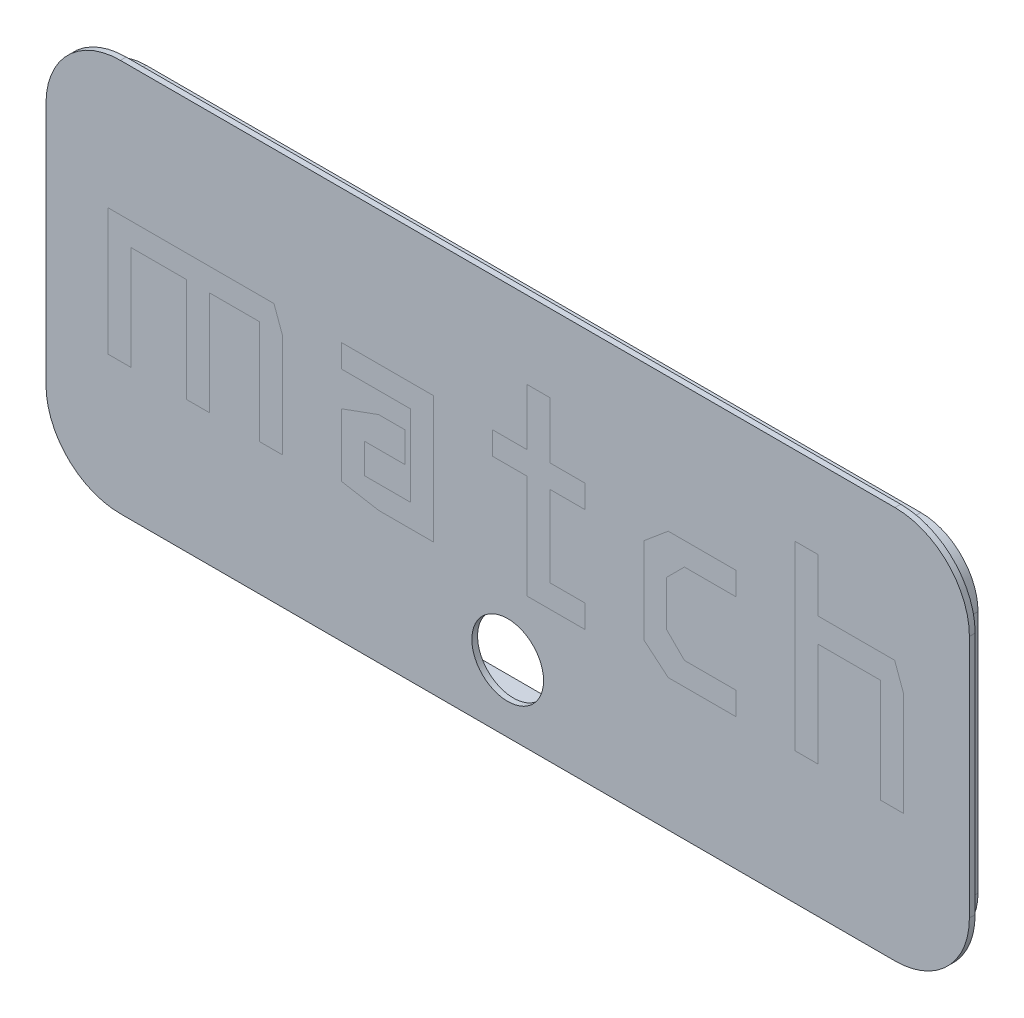
SolidWorks part; units mm, degrees
ref_plane "Ebene vorne" through (0, 0, 0) normal (0, 0, 1) x (1, 0, 0)
ref_plane "Ebene oben" through (0, 0, 0) normal (0, 1, 0) x (1, 0, 0)
ref_plane "Ebene rechts" through (0, 0, 0) normal (1, 0, 0) x (0, 0, -1)
sketch "Skizze1" plane through (0, 0, 1.6001) normal (0, 0, 1) x (1, 0, 0)
  line L0 (-27.8511, -4.4825) -> (-26.2511, -4.4825)
  line L1 (-26.2511, -4.4825) -> (-26.2511, 2.7565)
  line L2 (-26.2511, 2.7565) -> (-22.39, 2.7565)
  line L3 (-22.39, 2.7565) -> (-22.39, -4.4825)
  line L4 (-22.39, -4.4825) -> (-20.79, -4.4825)
  line L5 (-20.79, -4.4825) -> (-20.79, 2.7565)
  line L6 (-20.79, 2.7565) -> (-17.31, 2.7565)
  line L7 (-17.31, 2.7565) -> (-17.31, -4.4825)
  line L8 (-17.31, -4.4825) -> (-15.71, -4.4825)
  line L10 (-16.2924, 4.3565) -> (-27.8511, 4.3565)
  line L11 (-27.8511, 4.3565) -> (-27.8511, -4.4825)
  line L24 (-11.595, 4.3565) -> (-5.169, 4.3565)
  line L25 (-5.169, 4.3565) -> (-5.169, -4.4825)
  line L26 (-5.169, -4.4825) -> (-8.995, -4.4825)
  line L27 (-8.995, -4.4825) -> (-11.595, -4.0241)
  line L28 (-11.595, -4.0241) -> (-11.595, 0.3551)
  line L29 (-11.595, 0.3551) -> (-8.995, 1.3014)
  line L31 (-7.1585, -0.7995) -> (-9.995, -0.7995)
  line L32 (-9.995, -0.7995) -> (-9.995, -2.8825)
  line L33 (-9.995, -2.8825) -> (-6.769, -2.8825)
  line L34 (-6.769, -2.8825) -> (-6.769, 2.7565)
  line L35 (-6.769, 2.7565) -> (-11.595, 2.7565)
  line L36 (-11.595, 2.7565) -> (-11.595, 4.3565)
  line L50 (1.359, 8.2935) -> (1.359, 4.3565)
  line L51 (1.359, 4.3565) -> (-1.054, 4.3565)
  line L52 (-1.054, 4.3565) -> (-1.054, 2.7565)
  line L53 (-1.054, 2.7565) -> (1.359, 2.7565)
  line L54 (1.359, 2.7565) -> (1.359, -4.4825)
  line L55 (1.359, -4.4825) -> (5.372, -4.4825)
  line L56 (5.372, -4.4825) -> (5.372, -2.8825)
  line L57 (5.372, -2.8825) -> (2.959, -2.8825)
  line L58 (2.959, -2.8825) -> (2.959, 2.7565)
  line L59 (2.959, 2.7565) -> (5.372, 2.7565)
  line L60 (5.372, 2.7565) -> (5.372, 4.3565)
  line L61 (5.372, 4.3565) -> (2.959, 4.3565)
  line L62 (2.959, 4.3565) -> (2.959, 8.2935)
  line L63 (2.959, 8.2935) -> (1.359, 8.2935)
  line L64 (-16.01, 0.6435) -> (-16.01, 1.6435) construction
  line L65 (-27.5511, 4.0565) -> (-27.5511, 3.0565) construction
  line L66 (-26.5511, -1.7695) -> (-26.5511, -0.7695) construction
  line L67 (-22.09, 1.6435) -> (-22.09, 0.6435) construction
  line L68 (-21.09, 0.6435) -> (-21.09, 1.6435) construction
  line L69 (-20.312, 3.0565) -> (-19.312, 3.0565) construction
  line L70 (-15.71, 2.7565) -> (-16.2924, 4.3565)
  line L71 (-24.138, 4.0565) -> (-25.138, 4.0565) construction
  line L72 (-27.5511, -4.1825) -> (-26.5511, -4.1825) construction
  line L73 (-17.01, 1.6435) -> (-17.01, 0.6435) construction
  line L74 (20.028, 8.1665) -> (20.028, -4.4825)
  line L75 (20.028, -4.4825) -> (21.628, -4.4825)
  line L76 (21.628, -4.4825) -> (21.628, 2.7565)
  line L77 (21.628, 2.7565) -> (25.9971, 2.7565)
  line L78 (25.9971, 2.7565) -> (25.9971, -4.4825)
  line L79 (25.9971, -4.4825) -> (27.5971, -4.4825)
  line L80 (27.5971, -4.4825) -> (27.5971, 2.7565)
  line L83 (26.9783, 4.4565) -> (21.628, 4.4565)
  line L84 (21.628, 4.4565) -> (21.628, 8.1665)
  line L85 (21.628, 8.1665) -> (20.028, 8.1665)
  line L86 (15.913, 2.7565) -> (12.3216, 2.7565)
  line L87 (12.3216, 2.7565) -> (11.087, 1.5219)
  line L88 (11.087, 1.5219) -> (11.087, -1.6479)
  line L89 (11.087, -1.6479) -> (12.3216, -2.8825)
  line L90 (12.3216, -2.8825) -> (15.913, -2.8825)
  line L91 (15.913, -2.8825) -> (15.913, -4.4825)
  line L92 (15.913, -4.4825) -> (11.1914, -4.4825)
  line L93 (11.1914, -4.4825) -> (9.487, -3.0524)
  line L94 (9.487, -3.0524) -> (9.487, 2.9264)
  line L95 (9.487, 2.9264) -> (11.1914, 4.3565)
  line L96 (11.1914, 4.3565) -> (15.913, 4.3565)
  line L97 (15.913, 4.3565) -> (15.913, 2.7565)
  line L98 (-0.754, 4.0565) -> (-0.754, 3.0565) construction
  line L99 (0.246, 4.0565) -> (-0.754, 4.0565) construction
  line L100 (1.659, 5.1995) -> (1.659, 4.1995) construction
  line L101 (2.659, 7.9935) -> (1.659, 7.9935) construction
  line L102 (2.659, 6.9935) -> (2.659, 7.9935) construction
  line L103 (5.072, 3.0565) -> (5.072, 4.0565) construction
  line L104 (4.072, 3.0565) -> (5.072, 3.0565) construction
  line L105 (2.659, 1.4055) -> (2.659, 2.4055) construction
  line L106 (5.072, -4.1825) -> (5.072, -3.1825) construction
  line L107 (5.072, -3.1825) -> (4.072, -3.1825) construction
  line L108 (1.659, -4.1825) -> (2.659, -4.1825) construction
  line L109 (9.787, 0.3735) -> (9.787, -0.6265) construction
  line L110 (10.787, -0.6265) -> (10.787, 0.3735) construction
  line L111 (-11.295, 4.0565) -> (-11.295, 3.0565) construction
  line L112 (-10.295, 4.0565) -> (-11.295, 4.0565) construction
  line L113 (14.613, 3.0565) -> (15.613, 3.0565) construction
  line L114 (15.613, 3.0565) -> (15.613, 4.0565) construction
  line L115 (13.2, 4.0565) -> (12.2, 4.0565) construction
  line L116 (12.2, -4.1825) -> (13.2, -4.1825) construction
  line L117 (20.328, -0.2615) -> (20.328, -1.2615) construction
  line L118 (21.328, -1.2615) -> (21.328, -0.2615) construction
  line L119 (22.741, 3.0565) -> (23.741, 3.0565) construction
  line L120 (26.2971, 1.7705) -> (26.2971, 0.7705) construction
  line L121 (27.2971, 0.7705) -> (27.2971, 1.7705) construction
  line L122 (23.741, 4.0565) -> (22.741, 4.0565) construction
  line L123 (21.328, 7.8665) -> (20.328, 7.8665) construction
  line L124 (21.328, 6.8665) -> (21.328, 7.8665) construction
  line L125 (27.5971, 2.7565) -> (26.9783, 4.4565)
  line L126 (20.328, -4.1825) -> (21.328, -4.1825) construction
  line L127 (-15.71, -4.4825) -> (-15.71, 2.7565)
  line L129 (-11.295, 3.0565) -> (-10.295, 3.0565) construction
  line L130 (-11.295, -0.1345) -> (-11.295, -1.1345) construction
  line L131 (-8.882, -4.1825) -> (-7.882, -4.1825) construction
  line L132 (-5.469, 3.0565) -> (-5.469, 4.0565) construction
  line L134 (-6.469, 1.6435) -> (-6.469, 0.6435) construction
  line L135 (-7.882, -3.1825) -> (-8.882, -3.1825) construction
  line L136 (-10.295, -1.1345) -> (-10.295, -0.1345) construction
  line L137 (-8.995, 1.3014) -> (-7.1585, 1.3014)
  line L138 (-7.1585, 1.3014) -> (-7.1585, -0.7995)
  line L140 (-7.755, 0.5005) -> (-8.755, 0.5005) construction
  line L141 (-4.569, 4.7565) -> (-11.995, 4.7565)
  line L142 (-4.569, 4.7565) -> (-4.569, -5.0825)
  line L143 (-4.569, -5.0825) -> (-11.995, -5.0825)
  line L144 (-11.995, 4.7565) -> (-11.995, -5.0825)
  line L145 (-7.755, -0.4995) -> (-7.755, 0.5005) construction
  line L146 (-8.755, -0.4995) -> (-7.755, -0.4995) construction
  line L147 (-15.9423, 4.8565) -> (-28.3511, 4.8565)
  line L148 (-28.3511, 4.8565) -> (-28.3511, -4.9825)
  line L149 (-28.3511, -4.9825) -> (-25.7511, -4.9825)
  line L150 (-25.7511, -4.9825) -> (-25.7511, 2.2565)
  line L151 (-25.7511, 2.2565) -> (-22.89, 2.2565)
  line L152 (-22.89, 2.2565) -> (-22.89, -4.9825)
  line L153 (-22.89, -4.9825) -> (-20.29, -4.9825)
  line L154 (-20.29, -4.9825) -> (-20.29, 2.2565)
  line L155 (-20.29, 2.2565) -> (-17.81, 2.2565)
  line L156 (-17.81, 2.2565) -> (-17.81, -4.9825)
  line L157 (-17.81, -4.9825) -> (-15.21, -4.9825)
  line L158 (-15.21, -4.9825) -> (-15.21, 2.8447)
  line L159 (-15.21, 2.8447) -> (-15.9423, 4.8565)
  line L160 (5.872, 4.8565) -> (3.459, 4.8565)
  line L161 (3.459, 4.8565) -> (3.459, 8.7935)
  line L162 (3.459, 8.7935) -> (0.859, 8.7935)
  line L163 (0.859, 8.7935) -> (0.859, 4.8565)
  line L164 (0.859, 4.8565) -> (-1.554, 4.8565)
  line L165 (-1.554, 4.8565) -> (-1.554, 2.2565)
  line L166 (-1.554, 2.2565) -> (0.859, 2.2565)
  line L167 (0.859, 2.2565) -> (0.859, -4.9825)
  line L168 (0.859, -4.9825) -> (5.872, -4.9825)
  line L169 (5.872, -4.9825) -> (5.872, -2.3825)
  line L170 (5.872, -2.3825) -> (3.459, -2.3825)
  line L171 (3.459, -2.3825) -> (3.459, 2.2565)
  line L172 (3.459, 2.2565) -> (5.872, 2.2565)
  line L173 (5.872, 2.2565) -> (5.872, 4.8565)
  line L174 (11.0094, 4.8565) -> (16.413, 4.8565)
  line L175 (16.413, 4.8565) -> (16.413, 2.2565)
  line L176 (16.413, 2.2565) -> (12.5287, 2.2565)
  line L177 (12.5287, 2.2565) -> (11.587, 1.3148)
  line L178 (11.587, 1.3148) -> (11.587, -1.4408)
  line L179 (11.587, -1.4408) -> (12.5287, -2.3825)
  line L180 (12.5287, -2.3825) -> (16.413, -2.3825)
  line L181 (16.413, -2.3825) -> (16.413, -4.9825)
  line L182 (16.413, -4.9825) -> (11.0094, -4.9825)
  line L183 (11.0094, -4.9825) -> (8.987, -3.2856)
  line L184 (8.987, -3.2856) -> (8.987, 3.1596)
  line L185 (8.987, 3.1596) -> (11.0094, 4.8565)
  line L186 (27.2584, 4.8565) -> (22.028, 4.8565)
  line L187 (22.028, 4.8565) -> (22.028, 8.5665)
  line L188 (22.028, 8.5665) -> (19.628, 8.5665)
  line L189 (19.628, 8.5665) -> (19.628, -4.8825)
  line L190 (19.628, -4.8825) -> (22.028, -4.8825)
  line L191 (22.028, -4.8825) -> (22.028, 2.3565)
  line L192 (22.028, 2.3565) -> (25.5971, 2.3565)
  line L193 (25.5971, 2.3565) -> (25.5971, -4.8825)
  line L194 (25.5971, -4.8825) -> (27.9971, -4.8825)
  line L195 (27.9971, -4.8825) -> (27.9971, 2.827)
  line L196 (27.9971, 2.827) -> (27.2584, 4.8565)
  dimension "D1" = 0.3
  dimension "D2" = 0.3
  dimension "D3" = 0.3
  dimension "D4" = 0.3
  dimension "D5" = 0.3
  dimension "D7" = 0.3
  dimension "D8" = 0.3
  dimension "D9" = 0.3
  dimension "D10" = 0.3
  dimension "D11" = 0.3
  dimension "D12" = 0.3
  dimension "D13" = 0.3
  dimension "D14" = 0.3
  dimension "D15" = 0.3
  dimension "D16" = 0.3
  dimension "D17" = 0.3
  dimension "D18" = 0.3
  dimension "D19" = 0.3
  dimension "D20" = 0.3
  dimension "D21" = 0.3
  dimension "D22" = 0.3
  dimension "D23" = 0.3
  dimension "D24" = 0.3
  dimension "D25" = 0.3
  dimension "D26" = 0.3
  dimension "D27" = 130
  dimension "D28" = 135
  dimension "D29" = 0.4
  dimension "D30" = 0.3
  dimension "D31" = 0.3
  dimension "D32" = 0.3
  dimension "D33" = 0.3
  dimension "D34" = 0.3
  dimension "D35" = 0.3
  dimension "D36" = 0.4
  dimension "D37" = 0.3
  dimension "D38" = 0.3
  dimension "D39" = 20
  dimension "D40" = 0.3
  dimension "D6" = 0.3
  dimension "D41" = 200
  dimension "D42" = 0.3
  dimension "D43" = 0.3
  dimension "D44" = 0.3
  dimension "D45" = 0.3
  dimension "D46" = 0.3
  dimension "D47" = 0.3
  dimension "D48" = 0.3
  dimension "D49" = 0.3
  dimension "D50" = 0.3
  dimension "D51" = 110
  dimension "D52" = 0.8009
  dimension "D53" = 0.5965
  dimension "D54" = 0.3
  dimension "D55" = 2.6
  dimension "D56" = 0.4
  dimension "D58" = 0.6
  dimension "D59" = 0.4
  dimension "D57" = 10
  dimension "D64" = 2.6
  dimension "D65" = 0.6
  dimension "D60" = 0.5
  dimension "D61" = 0.5
  dimension "D62" = 0.5
  dimension "D63" = 0.4
extrude "Aufsatz-Linear austragen1" add sketch "Skizze1" along normal blind 1.4
sketch "Skizze2" plane through (0, 0, 3.0001) normal (0, 0, 1) x (1, 0, 0)
  line L0 (30.9874, 8.5) -> (30.9874, -8.5) construction
  line L1 (27.0001, -12.4873) -> (-27.0001, -12.4873) construction
  line L2 (-30.9874, -8.5) -> (-30.9874, 8.5) construction
  line L3 (-27.0001, 12.4873) -> (27.0001, 12.4873) construction
  line L4 (30.9874, 8.5) -> (30.9874, -8.5) construction
  line L5 (27.0001, -12.4873) -> (-27.0001, -12.4873) construction
  line L6 (-30.9874, -8.5) -> (-30.9874, 8.5) construction
  line L7 (-27.0001, 12.4873) -> (27.0001, 12.4873) construction
  line L8 (-27.0001, 13.6873) -> (27.0001, 13.6873)
  line L9 (32.1874, 8.5) -> (32.1874, -8.5)
  line L10 (27.0001, -13.6873) -> (-27.0001, -13.6873)
  line L11 (-32.1874, -8.5) -> (-32.1874, 8.5)
  arc A0 (30.9874, 8.5) -> (27.0001, 12.4873) centre (27.0001, 8.5) ccw construction
  arc A1 (27.0001, -12.4873) -> (30.9874, -8.5) centre (27.0001, -8.5) ccw construction
  arc A2 (-30.9874, -8.5) -> (-27.0001, -12.4873) centre (-27.0001, -8.5) ccw construction
  arc A3 (-27.0001, 12.4873) -> (-30.9874, 8.5) centre (-27.0001, 8.5) ccw construction
  arc A4 (30.9874, 8.5) -> (27.0001, 12.4873) centre (27.0001, 8.5) ccw construction
  arc A5 (27.0001, -12.4873) -> (30.9874, -8.5) centre (27.0001, -8.5) ccw construction
  arc A6 (-30.9874, -8.5) -> (-27.0001, -12.4873) centre (-27.0001, -8.5) ccw construction
  arc A7 (-27.0001, 12.4873) -> (-30.9874, 8.5) centre (-27.0001, 8.5) ccw construction
  circle A8 centre (0, -9.017) radius 2.5
  arc A9 (0.7218, -9.017) -> (-0.7218, -9.017) centre (0, -9.017) ccw construction
  arc A10 (0.7218, -9.017) -> (-0.7218, -9.017) centre (0, -9.017) ccw construction
  arc A11 (32.1874, 8.5) -> (27.0001, 13.6873) centre (27.0001, 8.5) ccw
  arc A12 (27.0001, -13.6873) -> (32.1874, -8.5) centre (27.0001, -8.5) ccw
  arc A13 (-32.1874, -8.5) -> (-27.0001, -13.6873) centre (-27.0001, -8.5) ccw
  arc A14 (-27.0001, 13.6873) -> (-32.1874, 8.5) centre (-27.0001, 8.5) ccw
  dimension "D1" = 5
  dimension "D2" = 1.2
extrude "Aufsatz-Linear austragen2" add sketch "Skizze2" along normal blind 0.4
sketch "Skizze3" plane through (0, 0, 3.0001) normal (0, 0, -1) x (-1, 0, 0)
  line L0 (-30.9874, 8.5) -> (-30.9874, -8.5) construction
  line L1 (-27.0001, -12.4873) -> (27.0001, -12.4873) construction
  line L2 (30.9874, -8.5) -> (30.9874, 8.5) construction
  line L3 (27.0001, 12.4873) -> (-27.0001, 12.4873) construction
  line L4 (-30.9874, 8.5) -> (-30.9874, -8.5)
  line L5 (-27.0001, -12.4873) -> (27.0001, -12.4873)
  line L6 (30.9874, -8.5) -> (30.9874, 8.5)
  line L7 (27.0001, 12.4873) -> (-27.0001, 12.4873)
  line L8 (27.0001, 11.6873) -> (-27.0001, 11.6873)
  line L9 (-30.1874, 8.5) -> (-30.1874, -8.5)
  line L10 (-27.0001, -11.6873) -> (27.0001, -11.6873)
  line L11 (30.1874, -8.5) -> (30.1874, 8.5)
  arc A0 (-27.0001, 12.4873) -> (-30.9874, 8.5) centre (-27.0001, 8.5) ccw construction
  arc A1 (-30.9874, -8.5) -> (-27.0001, -12.4873) centre (-27.0001, -8.5) ccw construction
  arc A2 (27.0001, -12.4873) -> (30.9874, -8.5) centre (27.0001, -8.5) ccw construction
  arc A3 (30.9874, 8.5) -> (27.0001, 12.4873) centre (27.0001, 8.5) ccw construction
  arc A4 (-27.0001, 12.4873) -> (-30.9874, 8.5) centre (-27.0001, 8.5) ccw
  arc A5 (-30.9874, -8.5) -> (-27.0001, -12.4873) centre (-27.0001, -8.5) ccw
  arc A6 (27.0001, -12.4873) -> (30.9874, -8.5) centre (27.0001, -8.5) ccw
  arc A7 (30.9874, 8.5) -> (27.0001, 12.4873) centre (27.0001, 8.5) ccw
  arc A8 (-27.0001, 11.6873) -> (-30.1874, 8.5) centre (-27.0001, 8.5) ccw
  arc A9 (-30.1874, -8.5) -> (-27.0001, -11.6873) centre (-27.0001, -8.5) ccw
  arc A10 (27.0001, -11.6873) -> (30.1874, -8.5) centre (27.0001, -8.5) ccw
  arc A11 (30.1874, 8.5) -> (27.0001, 11.6873) centre (27.0001, 8.5) ccw
  dimension "D1" = 0.8
extrude "Aufsatz-Linear austragen3" add sketch "Skizze3" along normal up to surface (1.4 mm away)
sketch "Skizze6" plane through (0, 0, 3.4001) normal (0, 0, 1) x (1, 0, 0)
  line L0 (-26.2511, -4.4825) -> (-27.8511, -4.4825) construction
  line L1 (-27.8511, -4.4825) -> (-27.8511, 4.3565) construction
  line L2 (-27.8511, 4.3565) -> (-16.2924, 4.3565) construction
  line L3 (-16.2924, 4.3565) -> (-15.71, 2.7565) construction
  line L4 (-15.71, 2.7565) -> (-15.71, -4.4825) construction
  line L5 (-15.71, -4.4825) -> (-17.31, -4.4825) construction
  line L6 (-17.31, -4.4825) -> (-17.31, 2.7565) construction
  line L7 (-17.31, 2.7565) -> (-20.79, 2.7565) construction
  line L8 (-20.79, 2.7565) -> (-20.79, -4.4825) construction
  line L9 (-20.79, -4.4825) -> (-22.39, -4.4825) construction
  line L10 (-22.39, -4.4825) -> (-22.39, 2.7565) construction
  line L11 (-22.39, 2.7565) -> (-26.2511, 2.7565) construction
  line L12 (-26.2511, 2.7565) -> (-26.2511, -4.4825) construction
  line L13 (-7.1585, 1.3014) -> (-7.1585, -0.7995) construction
  line L14 (-7.1585, -0.7995) -> (-9.995, -0.7995) construction
  line L15 (-9.995, -0.7995) -> (-9.995, -2.8825) construction
  line L16 (-9.995, -2.8825) -> (-6.769, -2.8825) construction
  line L17 (-6.769, -2.8825) -> (-6.769, 2.7565) construction
  line L18 (-6.769, 2.7565) -> (-11.595, 2.7565) construction
  line L19 (-11.595, 2.7565) -> (-11.595, 4.3565) construction
  line L20 (-11.595, 4.3565) -> (-5.169, 4.3565) construction
  line L21 (-5.169, 4.3565) -> (-5.169, -4.4825) construction
  line L22 (-5.169, -4.4825) -> (-8.995, -4.4825) construction
  line L23 (-8.995, -4.4825) -> (-11.595, -4.0241) construction
  line L24 (-11.595, -4.0241) -> (-11.595, 0.3551) construction
  line L25 (-11.595, 0.3551) -> (-8.995, 1.3014) construction
  line L26 (-8.995, 1.3014) -> (-7.1585, 1.3014) construction
  line L27 (1.359, 4.3565) -> (1.359, 8.2935) construction
  line L28 (1.359, 8.2935) -> (2.959, 8.2935) construction
  line L29 (2.959, 8.2935) -> (2.959, 4.3565) construction
  line L30 (2.959, 4.3565) -> (5.372, 4.3565) construction
  line L31 (5.372, 4.3565) -> (5.372, 2.7565) construction
  line L32 (5.372, 2.7565) -> (2.959, 2.7565) construction
  line L33 (2.959, 2.7565) -> (2.959, -2.8825) construction
  line L34 (2.959, -2.8825) -> (5.372, -2.8825) construction
  line L35 (5.372, -2.8825) -> (5.372, -4.4825) construction
  line L36 (5.372, -4.4825) -> (1.359, -4.4825) construction
  line L37 (1.359, -4.4825) -> (1.359, 2.7565) construction
  line L38 (1.359, 2.7565) -> (-1.054, 2.7565) construction
  line L39 (-1.054, 2.7565) -> (-1.054, 4.3565) construction
  line L40 (-1.054, 4.3565) -> (1.359, 4.3565) construction
  line L41 (11.1914, 4.3565) -> (15.913, 4.3565) construction
  line L42 (15.913, 4.3565) -> (15.913, 2.7565) construction
  line L43 (15.913, 2.7565) -> (12.3216, 2.7565) construction
  line L44 (12.3216, 2.7565) -> (11.087, 1.5219) construction
  line L45 (11.087, 1.5219) -> (11.087, -1.6479) construction
  line L46 (11.087, -1.6479) -> (12.3216, -2.8825) construction
  line L47 (12.3216, -2.8825) -> (15.913, -2.8825) construction
  line L48 (15.913, -2.8825) -> (15.913, -4.4825) construction
  line L49 (15.913, -4.4825) -> (11.1914, -4.4825) construction
  line L50 (11.1914, -4.4825) -> (9.487, -3.0524) construction
  line L51 (9.487, -3.0524) -> (9.487, 2.9264) construction
  line L52 (9.487, 2.9264) -> (11.1914, 4.3565) construction
  line L53 (20.028, -4.4825) -> (20.028, 8.1665) construction
  line L54 (20.028, 8.1665) -> (21.628, 8.1665) construction
  line L55 (21.628, 8.1665) -> (21.628, 4.4565) construction
  line L56 (21.628, 4.4565) -> (26.9783, 4.4565) construction
  line L57 (26.9783, 4.4565) -> (27.5971, 2.7565) construction
  line L58 (27.5971, 2.7565) -> (27.5971, -4.4825) construction
  line L59 (27.5971, -4.4825) -> (25.9971, -4.4825) construction
  line L60 (25.9971, -4.4825) -> (25.9971, 2.7565) construction
  line L61 (25.9971, 2.7565) -> (21.628, 2.7565) construction
  line L62 (21.628, 2.7565) -> (21.628, -4.4825) construction
  line L63 (21.628, -4.4825) -> (20.028, -4.4825) construction
  line L64 (-26.2511, -4.4825) -> (-27.8511, -4.4825)
  line L65 (-27.8511, -4.4825) -> (-27.8511, 4.3565)
  line L66 (-27.8511, 4.3565) -> (-16.2924, 4.3565)
  line L67 (-16.2924, 4.3565) -> (-15.71, 2.7565)
  line L68 (-15.71, 2.7565) -> (-15.71, -4.4825)
  line L69 (-15.71, -4.4825) -> (-17.31, -4.4825)
  line L70 (-17.31, -4.4825) -> (-17.31, 2.7565)
  line L71 (-17.31, 2.7565) -> (-20.79, 2.7565)
  line L72 (-20.79, 2.7565) -> (-20.79, -4.4825)
  line L73 (-20.79, -4.4825) -> (-22.39, -4.4825)
  line L74 (-22.39, -4.4825) -> (-22.39, 2.7565)
  line L75 (-22.39, 2.7565) -> (-26.2511, 2.7565)
  line L76 (-26.2511, 2.7565) -> (-26.2511, -4.4825)
  line L77 (-7.1585, 1.3014) -> (-7.1585, -0.7995)
  line L78 (-7.1585, -0.7995) -> (-9.995, -0.7995)
  line L79 (-9.995, -0.7995) -> (-9.995, -2.8825)
  line L80 (-9.995, -2.8825) -> (-6.769, -2.8825)
  line L81 (-6.769, -2.8825) -> (-6.769, 2.7565)
  line L82 (-6.769, 2.7565) -> (-11.595, 2.7565)
  line L83 (-11.595, 2.7565) -> (-11.595, 4.3565)
  line L84 (-11.595, 4.3565) -> (-5.169, 4.3565)
  line L85 (-5.169, 4.3565) -> (-5.169, -4.4825)
  line L86 (-5.169, -4.4825) -> (-8.995, -4.4825)
  line L87 (-8.995, -4.4825) -> (-11.595, -4.0241)
  line L88 (-11.595, -4.0241) -> (-11.595, 0.3551)
  line L89 (-11.595, 0.3551) -> (-8.995, 1.3014)
  line L90 (-8.995, 1.3014) -> (-7.1585, 1.3014)
  line L91 (1.359, 4.3565) -> (1.359, 8.2935)
  line L92 (1.359, 8.2935) -> (2.959, 8.2935)
  line L93 (2.959, 8.2935) -> (2.959, 4.3565)
  line L94 (2.959, 4.3565) -> (5.372, 4.3565)
  line L95 (5.372, 4.3565) -> (5.372, 2.7565)
  line L96 (5.372, 2.7565) -> (2.959, 2.7565)
  line L97 (2.959, 2.7565) -> (2.959, -2.8825)
  line L98 (2.959, -2.8825) -> (5.372, -2.8825)
  line L99 (5.372, -2.8825) -> (5.372, -4.4825)
  line L100 (5.372, -4.4825) -> (1.359, -4.4825)
  line L101 (1.359, -4.4825) -> (1.359, 2.7565)
  line L102 (1.359, 2.7565) -> (-1.054, 2.7565)
  line L103 (-1.054, 2.7565) -> (-1.054, 4.3565)
  line L104 (-1.054, 4.3565) -> (1.359, 4.3565)
  line L105 (11.1914, 4.3565) -> (15.913, 4.3565)
  line L106 (15.913, 4.3565) -> (15.913, 2.7565)
  line L107 (15.913, 2.7565) -> (12.3216, 2.7565)
  line L108 (12.3216, 2.7565) -> (11.087, 1.5219)
  line L109 (11.087, 1.5219) -> (11.087, -1.6479)
  line L110 (11.087, -1.6479) -> (12.3216, -2.8825)
  line L111 (12.3216, -2.8825) -> (15.913, -2.8825)
  line L112 (15.913, -2.8825) -> (15.913, -4.4825)
  line L113 (15.913, -4.4825) -> (11.1914, -4.4825)
  line L114 (11.1914, -4.4825) -> (9.487, -3.0524)
  line L115 (9.487, -3.0524) -> (9.487, 2.9264)
  line L116 (9.487, 2.9264) -> (11.1914, 4.3565)
  line L117 (20.028, -4.4825) -> (20.028, 8.1665)
  line L118 (20.028, 8.1665) -> (21.628, 8.1665)
  line L119 (21.628, 8.1665) -> (21.628, 4.4565)
  line L120 (21.628, 4.4565) -> (26.9783, 4.4565)
  line L121 (26.9783, 4.4565) -> (27.5971, 2.7565)
  line L122 (27.5971, 2.7565) -> (27.5971, -4.4825)
  line L123 (27.5971, -4.4825) -> (25.9971, -4.4825)
  line L124 (25.9971, -4.4825) -> (25.9971, 2.7565)
  line L125 (25.9971, 2.7565) -> (21.628, 2.7565)
  line L126 (21.628, 2.7565) -> (21.628, -4.4825)
  line L127 (21.628, -4.4825) -> (20.028, -4.4825)
sketch "Skizze4" plane through (0, 0, 3.0001) normal (0, 0, -1) x (-1, 0, 0)
  line L0 (26.2511, -4.4825) -> (27.8511, -4.4825) construction
  line L1 (27.8511, -4.4825) -> (27.8511, 4.3565) construction
  line L2 (27.8511, 4.3565) -> (16.2924, 4.3565) construction
  line L3 (16.2924, 4.3565) -> (15.71, 2.7565) construction
  line L4 (15.71, 2.7565) -> (15.71, -4.4825) construction
  line L5 (15.71, -4.4825) -> (17.31, -4.4825) construction
  line L6 (17.31, -4.4825) -> (17.31, 2.7565) construction
  line L7 (17.31, 2.7565) -> (20.79, 2.7565) construction
  line L8 (20.79, 2.7565) -> (20.79, -4.4825) construction
  line L9 (20.79, -4.4825) -> (22.39, -4.4825) construction
  line L10 (22.39, -4.4825) -> (22.39, 2.7565) construction
  line L11 (22.39, 2.7565) -> (26.2511, 2.7565) construction
  line L12 (26.2511, 2.7565) -> (26.2511, -4.4825) construction
  line L13 (7.1585, 1.3014) -> (7.1585, -0.7995) construction
  line L14 (7.1585, -0.7995) -> (9.995, -0.7995) construction
  line L15 (9.995, -0.7995) -> (9.995, -2.8825) construction
  line L16 (9.995, -2.8825) -> (6.769, -2.8825) construction
  line L17 (6.769, -2.8825) -> (6.769, 2.7565) construction
  line L18 (6.769, 2.7565) -> (11.595, 2.7565) construction
  line L19 (11.595, 2.7565) -> (11.595, 4.3565) construction
  line L20 (11.595, 4.3565) -> (5.169, 4.3565) construction
  line L21 (5.169, 4.3565) -> (5.169, -4.4825) construction
  line L22 (5.169, -4.4825) -> (8.995, -4.4825) construction
  line L23 (8.995, -4.4825) -> (11.595, -4.0241) construction
  line L24 (11.595, -4.0241) -> (11.595, 0.3551) construction
  line L25 (11.595, 0.3551) -> (8.995, 1.3014) construction
  line L26 (8.995, 1.3014) -> (7.1585, 1.3014) construction
  line L27 (-1.359, 4.3565) -> (-1.359, 8.2935) construction
  line L28 (-1.359, 8.2935) -> (-2.959, 8.2935) construction
  line L29 (-2.959, 8.2935) -> (-2.959, 4.3565) construction
  line L30 (-2.959, 4.3565) -> (-5.372, 4.3565) construction
  line L31 (-5.372, 4.3565) -> (-5.372, 2.7565) construction
  line L32 (-5.372, 2.7565) -> (-2.959, 2.7565) construction
  line L33 (-2.959, 2.7565) -> (-2.959, -2.8825) construction
  line L34 (-2.959, -2.8825) -> (-5.372, -2.8825) construction
  line L35 (-5.372, -2.8825) -> (-5.372, -4.4825) construction
  line L36 (-5.372, -4.4825) -> (-1.359, -4.4825) construction
  line L37 (-1.359, -4.4825) -> (-1.359, 2.7565) construction
  line L38 (-1.359, 2.7565) -> (1.054, 2.7565) construction
  line L39 (1.054, 2.7565) -> (1.054, 4.3565) construction
  line L40 (1.054, 4.3565) -> (-1.359, 4.3565) construction
  line L41 (-11.1914, 4.3565) -> (-15.913, 4.3565) construction
  line L42 (-15.913, 4.3565) -> (-15.913, 2.7565) construction
  line L43 (-15.913, 2.7565) -> (-12.3216, 2.7565) construction
  line L44 (-12.3216, 2.7565) -> (-11.087, 1.5219) construction
  line L45 (-11.087, 1.5219) -> (-11.087, -1.6479) construction
  line L46 (-11.087, -1.6479) -> (-12.3216, -2.8825) construction
  line L47 (-12.3216, -2.8825) -> (-15.913, -2.8825) construction
  line L48 (-15.913, -2.8825) -> (-15.913, -4.4825) construction
  line L49 (-15.913, -4.4825) -> (-11.1914, -4.4825) construction
  line L50 (-11.1914, -4.4825) -> (-9.487, -3.0524) construction
  line L51 (-9.487, -3.0524) -> (-9.487, 2.9264) construction
  line L52 (-9.487, 2.9264) -> (-11.1914, 4.3565) construction
  line L53 (-20.028, -4.4825) -> (-20.028, 8.1665) construction
  line L54 (-20.028, 8.1665) -> (-21.628, 8.1665) construction
  line L55 (-21.628, 8.1665) -> (-21.628, 4.4565) construction
  line L56 (-21.628, 4.4565) -> (-26.9783, 4.4565) construction
  line L57 (-26.9783, 4.4565) -> (-27.5971, 2.7565) construction
  line L58 (-27.5971, 2.7565) -> (-27.5971, -4.4825) construction
  line L59 (-27.5971, -4.4825) -> (-25.9971, -4.4825) construction
  line L60 (-25.9971, -4.4825) -> (-25.9971, 2.7565) construction
  line L61 (-25.9971, 2.7565) -> (-21.628, 2.7565) construction
  line L62 (-21.628, 2.7565) -> (-21.628, -4.4825) construction
  line L63 (-21.628, -4.4825) -> (-20.028, -4.4825) construction
  line L64 (26.2511, -4.4825) -> (27.8511, -4.4825)
  line L65 (27.8511, -4.4825) -> (27.8511, 4.3565)
  line L66 (27.8511, 4.3565) -> (16.2924, 4.3565)
  line L67 (16.2924, 4.3565) -> (15.71, 2.7565)
  line L68 (15.71, 2.7565) -> (15.71, -4.4825)
  line L69 (15.71, -4.4825) -> (17.31, -4.4825)
  line L70 (17.31, -4.4825) -> (17.31, 2.7565)
  line L71 (17.31, 2.7565) -> (20.79, 2.7565)
  line L72 (20.79, 2.7565) -> (20.79, -4.4825)
  line L73 (20.79, -4.4825) -> (22.39, -4.4825)
  line L74 (22.39, -4.4825) -> (22.39, 2.7565)
  line L75 (22.39, 2.7565) -> (26.2511, 2.7565)
  line L76 (26.2511, 2.7565) -> (26.2511, -4.4825)
  line L77 (7.1585, 1.3014) -> (7.1585, -0.7995)
  line L78 (7.1585, -0.7995) -> (9.995, -0.7995)
  line L79 (9.995, -0.7995) -> (9.995, -2.8825)
  line L80 (9.995, -2.8825) -> (6.769, -2.8825)
  line L81 (6.769, -2.8825) -> (6.769, 2.7565)
  line L82 (6.769, 2.7565) -> (11.595, 2.7565)
  line L83 (11.595, 2.7565) -> (11.595, 4.3565)
  line L84 (11.595, 4.3565) -> (5.169, 4.3565)
  line L85 (5.169, 4.3565) -> (5.169, -4.4825)
  line L86 (5.169, -4.4825) -> (8.995, -4.4825)
  line L87 (8.995, -4.4825) -> (11.595, -4.0241)
  line L88 (11.595, -4.0241) -> (11.595, 0.3551)
  line L89 (11.595, 0.3551) -> (8.995, 1.3014)
  line L90 (8.995, 1.3014) -> (7.1585, 1.3014)
  line L91 (-1.359, 4.3565) -> (-1.359, 8.2935)
  line L92 (-1.359, 8.2935) -> (-2.959, 8.2935)
  line L93 (-2.959, 8.2935) -> (-2.959, 4.3565)
  line L94 (-2.959, 4.3565) -> (-5.372, 4.3565)
  line L95 (-5.372, 4.3565) -> (-5.372, 2.7565)
  line L96 (-5.372, 2.7565) -> (-2.959, 2.7565)
  line L97 (-2.959, 2.7565) -> (-2.959, -2.8825)
  line L98 (-2.959, -2.8825) -> (-5.372, -2.8825)
  line L99 (-5.372, -2.8825) -> (-5.372, -4.4825)
  line L100 (-5.372, -4.4825) -> (-1.359, -4.4825)
  line L101 (-1.359, -4.4825) -> (-1.359, 2.7565)
  line L102 (-1.359, 2.7565) -> (1.054, 2.7565)
  line L103 (1.054, 2.7565) -> (1.054, 4.3565)
  line L104 (1.054, 4.3565) -> (-1.359, 4.3565)
  line L105 (-11.1914, 4.3565) -> (-15.913, 4.3565)
  line L106 (-15.913, 4.3565) -> (-15.913, 2.7565)
  line L107 (-15.913, 2.7565) -> (-12.3216, 2.7565)
  line L108 (-12.3216, 2.7565) -> (-11.087, 1.5219)
  line L109 (-11.087, 1.5219) -> (-11.087, -1.6479)
  line L110 (-11.087, -1.6479) -> (-12.3216, -2.8825)
  line L111 (-12.3216, -2.8825) -> (-15.913, -2.8825)
  line L112 (-15.913, -2.8825) -> (-15.913, -4.4825)
  line L113 (-15.913, -4.4825) -> (-11.1914, -4.4825)
  line L114 (-11.1914, -4.4825) -> (-9.487, -3.0524)
  line L115 (-9.487, -3.0524) -> (-9.487, 2.9264)
  line L116 (-9.487, 2.9264) -> (-11.1914, 4.3565)
  line L117 (-20.028, -4.4825) -> (-20.028, 8.1665)
  line L118 (-20.028, 8.1665) -> (-21.628, 8.1665)
  line L119 (-21.628, 8.1665) -> (-21.628, 4.4565)
  line L120 (-21.628, 4.4565) -> (-26.9783, 4.4565)
  line L121 (-26.9783, 4.4565) -> (-27.5971, 2.7565)
  line L122 (-27.5971, 2.7565) -> (-27.5971, -4.4825)
  line L123 (-27.5971, -4.4825) -> (-25.9971, -4.4825)
  line L124 (-25.9971, -4.4825) -> (-25.9971, 2.7565)
  line L125 (-25.9971, 2.7565) -> (-21.628, 2.7565)
  line L126 (-21.628, 2.7565) -> (-21.628, -4.4825)
  line L127 (-21.628, -4.4825) -> (-20.028, -4.4825)
extrude "Schnitt-Linear austragen1" cut sketch "Skizze4" against normal through all
extrude "Aufsatz-Linear austragen4" add sketch "Skizze6" against normal blind 0.4 separate body
equation "\"D2@Skizze1\"=\"D1@Skizze1\""
equation "\"D3@Skizze1\"=\"D1@Skizze1\""
equation "\"D4@Skizze1\"=\"D1@Skizze1\""
equation "\"D5@Skizze1\"=\"D1@Skizze1\""
equation "\"D7@Skizze1\"=\"D1@Skizze1\""
equation "\"D8@Skizze1\"=\"D1@Skizze1\""
equation "\"D9@Skizze1\"=\"D1@Skizze1\""
equation "\"D11@Skizze1\"=\"D10@Skizze1\""
equation "\"D12@Skizze1\"=\"D10@Skizze1\""
equation "\"D13@Skizze1\"=\"D10@Skizze1\""
equation "\"D14@Skizze1\"=\"D10@Skizze1\""
equation "\"D15@Skizze1\"=\"D10@Skizze1\""
equation "\"D16@Skizze1\"=\"D10@Skizze1\""
equation "\"D17@Skizze1\"=\"D10@Skizze1\""
equation "\"D18@Skizze1\"=\"D10@Skizze1\""
equation "\"D20@Skizze1\"=\"D10@Skizze1\""
equation "\"D22@Skizze1\"=\"D21@Skizze1\""
equation "\"D23@Skizze1\"=\"D21@Skizze1\""
equation "\"D24@Skizze1\"=\"D21@Skizze1\""
equation "\"D25@Skizze1\"=\"D21@Skizze1\""
equation "\"D26@Skizze1\"=\"D21@Skizze1\""
equation "\"D33@Skizze1\"=\"D31@Skizze1\""
equation "\"D34@Skizze1\"=\"D31@Skizze1\""
equation "\"D35@Skizze1\"=\"D31@Skizze1\""
equation "\"D37@Skizze1\"=\"D31@Skizze1\""
equation "\"D38@Skizze1\"=\"D31@Skizze1\""
equation "\"D40@Skizze1\"=\"D31@Skizze1\""
equation "\"D32@Skizze1\"=\"D31@Skizze1\""
equation "\"D6@Skizze1\"=\"D1@Skizze1\""
equation "\"D43@Skizze1\"=\"D42@Skizze1\""
equation "\"D44@Skizze1\"=\"D42@Skizze1\""
equation "\"D45@Skizze1\"=\"D44@Skizze1\""
equation "\"D46@Skizze1\"=\"D42@Skizze1\""
equation "\"D47@Skizze1\"=\"D42@Skizze1\""
equation "\"D48@Skizze1\"=\"D42@Skizze1\""
equation "\"D49@Skizze1\"=\"D42@Skizze1\""
equation "\"D50@Skizze1\"=\"D42@Skizze1\""
equation "\"D54@Skizze1\"=\"D42@Skizze1\""
equation "\"D19@Skizze1\"=\"D10@Skizze1\""
